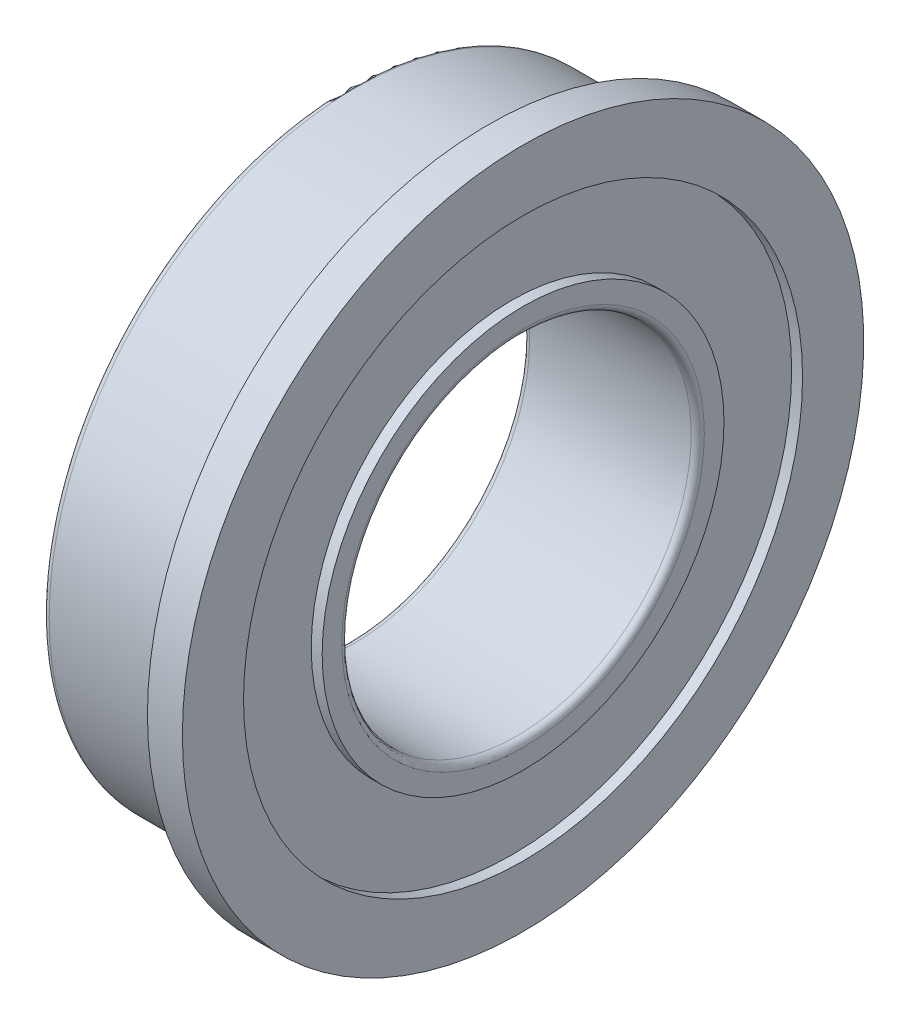
SolidWorks part; units mm, degrees
ref_plane "Front Plane" through (0, 0, 0) normal (0, 0, 1) x (1, 0, 0)
ref_plane "Top Plane" through (0, 0, 0) normal (0, 1, 0) x (1, 0, 0)
ref_plane "Right Plane" through (0, 0, 0) normal (1, 0, 0) x (0, 0, -1)
sketch "Sketch1" plane through (0, 0, 0) normal (0, 0, 1) x (1, 0, 0)
  line L0 (-3.2, 0) -> (0.8, 0) construction
  line L1 (0, 7.2) -> (0, 7.8)
  line L2 (0, 7.8) -> (0.8, 7.8)
  line L3 (0.8, 7.8) -> (0.8, 6.4)
  line L4 (0.8, 4) -> (-3.2, 4)
  line L5 (-3.2, 4) -> (-3.2, 4.6)
  line L6 (-3.2, 7) -> (-0.2, 7)
  line L7 (-3.2, 6.4) -> (-2.95, 6.4)
  line L8 (-2.95, 6.4) -> (-2.95, 4.6)
  line L9 (-2.95, 4.6) -> (-3.2, 4.6)
  line L10 (0.8, 6.4) -> (0.55, 6.4)
  line L11 (0.55, 6.4) -> (0.55, 4.6)
  line L12 (0.55, 4.6) -> (0.8, 4.6)
  line L13 (-3.2, 6.4) -> (-3.2, 7)
  line L14 (0.8, 4.6) -> (0.8, 4)
  arc A0 (-0.2, 7) -> (0, 7.2) centre (0, 7) ccw
  dimension "FIX_1" = 0.2
  dimension "D_s" = 8
  dimension "C" = 0.8
  dimension "MSM_2" = 9.2
  dimension "MSM_1" = 12.8
  dimension "D" = 14
  dimension "D1." = 15.6
  dimension "B" = 4
  dimension "MSM_3" = 0.25
revolve "Revolve1" add sketch "Sketch1" angle 360 about L0
fillet "Fillet1" radius 0.15 3 edges at (0.8, 0, 4) (-3.2, 0, 4) (-3.2, 0, 7)
